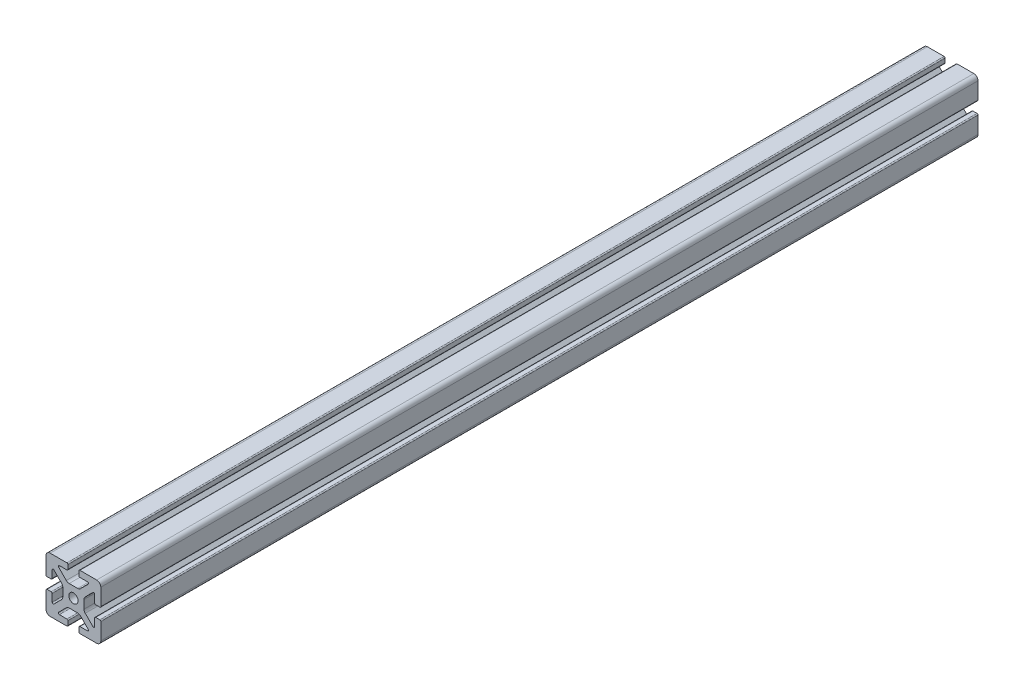
SolidWorks part; units mm, degrees
ref_plane "Front Plane" through (0, 0, 0) normal (0, 0, 1) x (1, 0, 0)
ref_plane "Top Plane" through (0, 0, 0) normal (0, 1, 0) x (1, 0, 0)
ref_plane "Right Plane" through (0, 0, 0) normal (1, 0, 0) x (0, 0, -1)
sketch "Sketch1" plane through (0, 0, 0) normal (0, 0, 1) x (1, 0, 0)
  line L2 (-20, 16.952) -> (-20, 4.7625)
  line L3 (-16.952, 20) -> (-4.7625, 20)
  line L4 (-4.0005, 19.238) -> (-4.0005, 16.2662)
  line L5 (-4.7625, 15.5042) -> (-10.2235, 15.5042)
  line L6 (-10.7623, 14.2034) -> (-5.194, 8.6351)
  line L7 (-14.2034, 10.7623) -> (-8.6351, 5.194)
  line L8 (-15.5042, 10.2235) -> (-15.5042, 4.7625)
  line L9 (-16.2662, 4.0005) -> (-19.238, 4.0005)
  line L11 (-3.0746, 7.7572) -> (3.0746, 7.7572)
  line L12 (-7.7572, 3.0746) -> (-7.7572, -3.0746)
  line L13 (16.2662, 4.0005) -> (19.238, 4.0005)
  line L14 (15.5042, 10.2235) -> (15.5042, 4.7625)
  line L15 (20, 16.952) -> (20, 4.7625)
  line L16 (16.952, 20) -> (4.7625, 20)
  line L17 (4.0005, 19.238) -> (4.0005, 16.2662)
  line L18 (4.7625, 15.5042) -> (10.2235, 15.5042)
  line L19 (7.7572, 3.0746) -> (7.7572, -3.0746)
  line L20 (10.7623, 14.2034) -> (5.194, 8.6351)
  line L21 (14.2034, 10.7623) -> (8.6351, 5.194)
  line L22 (-16.2662, -4.0005) -> (-19.238, -4.0005)
  line L23 (-15.5042, -10.2235) -> (-15.5042, -4.7625)
  line L24 (-14.2034, -10.7623) -> (-8.6351, -5.194)
  line L25 (-10.7623, -14.2034) -> (-5.194, -8.6351)
  line L26 (-4.7625, -15.5042) -> (-10.2235, -15.5042)
  line L27 (-4.0005, -19.238) -> (-4.0005, -16.2662)
  line L28 (-16.952, -20) -> (-4.7625, -20)
  line L29 (-20, -16.952) -> (-20, -4.7625)
  line L30 (20, -16.952) -> (20, -4.7625)
  line L31 (16.952, -20) -> (4.7625, -20)
  line L32 (4.0005, -19.238) -> (4.0005, -16.2662)
  line L33 (4.7625, -15.5042) -> (10.2235, -15.5042)
  line L34 (10.7623, -14.2034) -> (5.194, -8.6351)
  line L35 (14.2034, -10.7623) -> (8.6351, -5.194)
  line L36 (15.5042, -10.2235) -> (15.5042, -4.7625)
  line L37 (16.2662, -4.0005) -> (19.238, -4.0005)
  line L38 (-3.0746, -7.7572) -> (3.0746, -7.7572)
  circle A0 centre (0, 0) radius 3.4036
  arc A1 (-20, 16.952) -> (-16.952, 20) centre (-16.952, 16.952) cw
  arc A2 (-14.2034, 10.7623) -> (-15.5042, 10.2235) centre (-14.7422, 10.2235) ccw
  arc A3 (-10.2235, 15.5042) -> (-10.7623, 14.2034) centre (-10.2235, 14.7422) ccw
  arc A4 (-4.7625, 20) -> (-4.0005, 19.238) centre (-4.7625, 19.238) cw
  arc A5 (-20, 4.7625) -> (-19.238, 4.0005) centre (-19.238, 4.7625) ccw
  arc A6 (-15.5042, 4.7625) -> (-16.2662, 4.0005) centre (-16.2662, 4.7625) cw
  arc A7 (-4.0005, 16.2662) -> (-4.7625, 15.5042) centre (-4.7625, 16.2662) cw
  arc A8 (-3.0746, 7.7572) -> (-5.194, 8.6351) centre (-3.0746, 10.7544) cw
  arc A9 (-7.7572, 3.0746) -> (-8.6351, 5.194) centre (-10.7544, 3.0746) ccw
  arc A10 (15.5042, 4.7625) -> (16.2662, 4.0005) centre (16.2662, 4.7625) ccw
  arc A11 (20, 4.7625) -> (19.238, 4.0005) centre (19.238, 4.7625) cw
  arc A12 (20, 16.952) -> (16.952, 20) centre (16.952, 16.952) ccw
  arc A13 (4.7625, 20) -> (4.0005, 19.238) centre (4.7625, 19.238) ccw
  arc A14 (4.0005, 16.2662) -> (4.7625, 15.5042) centre (4.7625, 16.2662) ccw
  arc A15 (3.0746, 7.7572) -> (5.194, 8.6351) centre (3.0746, 10.7544) ccw
  arc A16 (7.7572, 3.0746) -> (8.6351, 5.194) centre (10.7544, 3.0746) cw
  arc A17 (14.2034, 10.7623) -> (15.5042, 10.2235) centre (14.7422, 10.2235) cw
  arc A18 (10.2235, 15.5042) -> (10.7623, 14.2034) centre (10.2235, 14.7422) cw
  arc A19 (-7.7572, -3.0746) -> (-8.6351, -5.194) centre (-10.7544, -3.0746) cw
  arc A20 (-3.0746, -7.7572) -> (-5.194, -8.6351) centre (-3.0746, -10.7544) ccw
  arc A21 (-4.0005, -16.2662) -> (-4.7625, -15.5042) centre (-4.7625, -16.2662) ccw
  arc A22 (-15.5042, -4.7625) -> (-16.2662, -4.0005) centre (-16.2662, -4.7625) ccw
  arc A23 (-20, -4.7625) -> (-19.238, -4.0005) centre (-19.238, -4.7625) cw
  arc A24 (-4.7625, -20) -> (-4.0005, -19.238) centre (-4.7625, -19.238) ccw
  arc A25 (-10.2235, -15.5042) -> (-10.7623, -14.2034) centre (-10.2235, -14.7422) cw
  arc A26 (-14.2034, -10.7623) -> (-15.5042, -10.2235) centre (-14.7422, -10.2235) cw
  arc A27 (-20, -16.952) -> (-16.952, -20) centre (-16.952, -16.952) ccw
  arc A28 (20, -16.952) -> (16.952, -20) centre (16.952, -16.952) cw
  arc A29 (14.2034, -10.7623) -> (15.5042, -10.2235) centre (14.7422, -10.2235) ccw
  arc A30 (10.2235, -15.5042) -> (10.7623, -14.2034) centre (10.2235, -14.7422) ccw
  arc A31 (4.7625, -20) -> (4.0005, -19.238) centre (4.7625, -19.238) cw
  arc A32 (20, -4.7625) -> (19.238, -4.0005) centre (19.238, -4.7625) ccw
  arc A33 (15.5042, -4.7625) -> (16.2662, -4.0005) centre (16.2662, -4.7625) cw
  arc A34 (4.0005, -16.2662) -> (4.7625, -15.5042) centre (4.7625, -16.2662) cw
  arc A35 (3.0746, -7.7572) -> (5.194, -8.6351) centre (3.0746, -10.7544) cw
  arc A36 (7.7572, -3.0746) -> (8.6351, -5.194) centre (10.7544, -3.0746) ccw
extrude "Boss-Extrude1" add sketch "Sketch1" along normal mid plane 640
